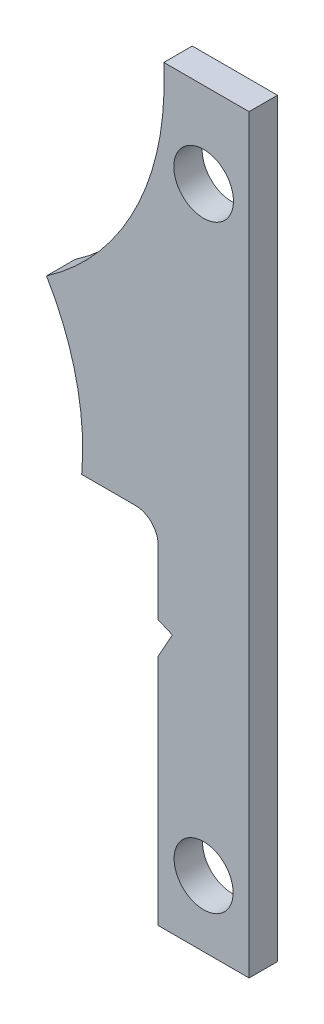
SolidWorks part; units mm, degrees
ref_plane "Front Plane" through (0, 0, 0) normal (0, 0, 1) x (1, 0, 0)
ref_plane "Top Plane" through (0, 0, 0) normal (0, 1, 0) x (1, 0, 0)
ref_plane "Right Plane" through (0, 0, 0) normal (1, 0, 0) x (0, 0, -1)
sketch "Model" plane through (0, 0, 0) normal (0, 0, 1) x (1, 0, 0)
  line L0 (869.6, 129.8) -> (854.6, 129.8)
  line L1 (854.6, 129.8) -> (854.6, 124.8)
  line L2 (820.0281, 59.8) -> (849.6, 59.8)
  line L3 (853.6, 55.8) -> (853.6, 44.4002)
  line L4 (853.6, 44.4002) -> (856.1, 43.3)
  line L5 (856.1, 43.3) -> (853.6, 38.8294)
  line L6 (853.6, 38.8294) -> (853.6, -2.2)
  line L7 (853.6, -2.2) -> (869.6, -2.2)
  line L8 (869.6, -2.2) -> (869.6, 129.8)
  arc A0 (815.1233, 79.1972) -> (854.6, 124.8) centre (806.7231, 126.3571) ccw
  arc A1 (820.0281, 59.8) -> (815.1233, 79.1972) centre (795.0764, 63.8094) ccw
  arc A2 (853.6, 55.8) -> (849.6, 59.8) centre (849.6, 55.8) ccw
  circle A3 centre (861.6, 9.3915) radius 5.1919
  circle A4 centre (861.6, 114.8) radius 5.25
extrude "Boss-Extrude1" add sketch "Model" along normal blind 5
sketch "Sketch3" plane through (0, 0, 0) normal (0, 0, -1) x (-1, 0, 0)
  circle A0 centre (-795.0764, 63.8094) radius 45.25
extrude "Cut-Extrude1" cut sketch "Sketch3" against normal blind 6
